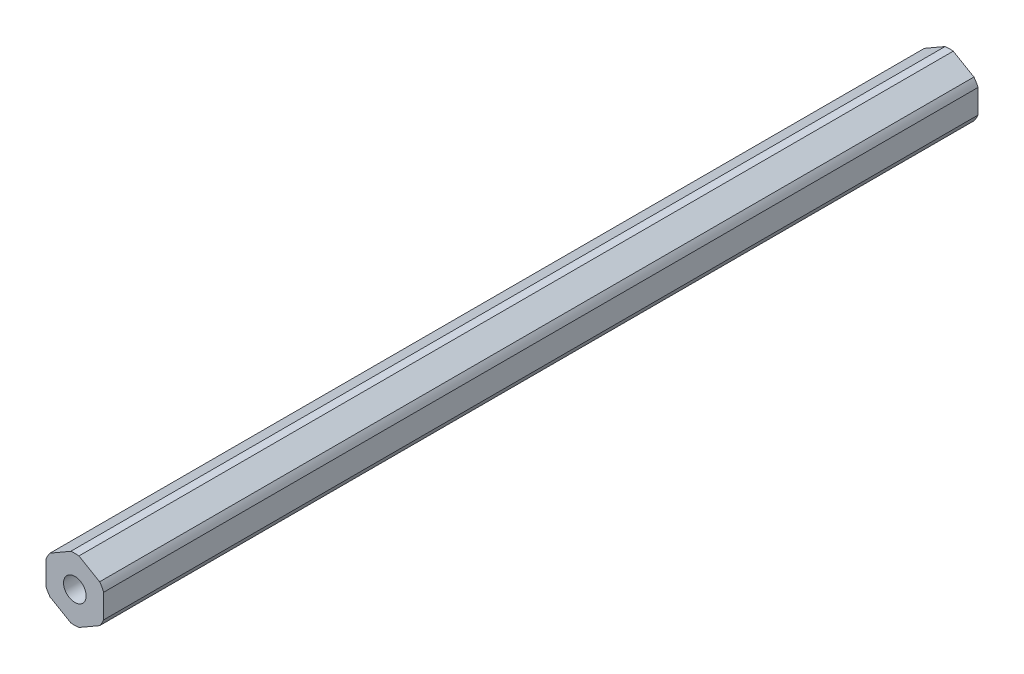
SolidWorks part; units mm, degrees
material "7075-T6 (SN)"
ref_plane "Front Plane" through (0, 0, 0) normal (0, 0, 1) x (1, 0, 0)
ref_plane "Top Plane" through (0, 0, 0) normal (0, 1, 0) x (1, 0, 0)
ref_plane "Right Plane" through (0, 0, 0) normal (1, 0, 0) x (0, 0, -1)
sketch "Sketch1" plane through (0, 0, 0) normal (0, 0, 1) x (1, 0, 0)
  line L1 (-0.893, 6.8168) -> (-5.457, 4.1818)
  line L2 (-6.35, 2.635) -> (-6.35, -2.635)
  line L3 (-5.457, -4.1818) -> (-0.893, -6.8168)
  line L4 (0.893, -6.8168) -> (5.457, -4.1818)
  line L5 (6.35, -2.635) -> (6.35, 2.635)
  line L6 (5.457, 4.1818) -> (0.893, 6.8168)
  arc A0 (-5.457, 4.1818) -> (-6.35, 2.635) centre (0, 0) ccw
  circle A1 centre (0, 0) radius 6.35 construction
  arc A2 (0.893, 6.8168) -> (-0.893, 6.8168) centre (0, 0) ccw
  arc A3 (6.35, 2.635) -> (5.457, 4.1818) centre (0, 0) ccw
  arc A4 (-6.35, -2.635) -> (-5.457, -4.1818) centre (0, 0) ccw
  arc A5 (-0.893, -6.8168) -> (0.893, -6.8168) centre (0, 0) ccw
  arc A6 (5.457, -4.1818) -> (6.35, -2.635) centre (0, 0) ccw
  dimension "D1" = 13.75
  dimension "D2" = 12.7
extrude "Boss-Extrude1" add sketch "Sketch1" along normal blind 192.405
sketch "Sketch2" plane through (0, 0, 0) normal (0, 0, -1) x (-1, 0, 0)
  circle A0 centre (0, 0) radius 2.4892
  dimension "D1" = 4.9784
extrude "Cut-Extrude1" cut sketch "Sketch2" against normal through all and the other way through all
